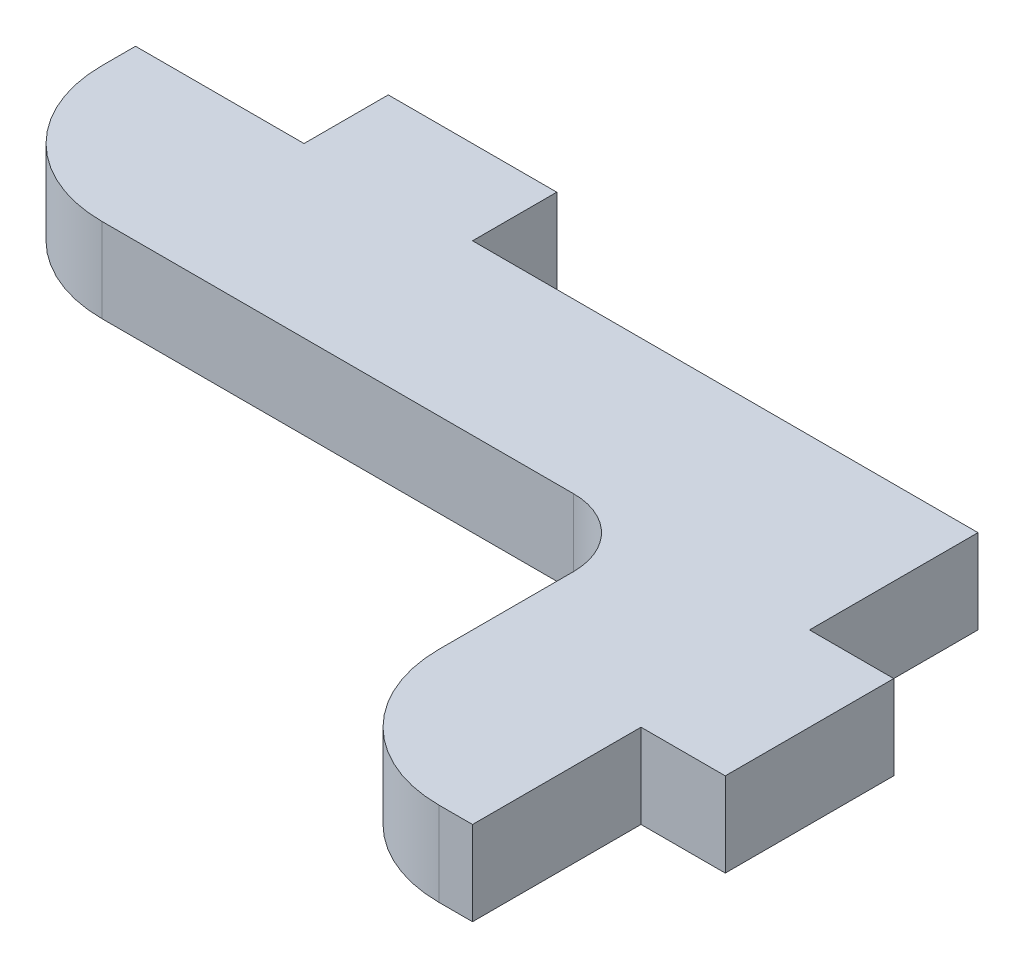
SolidWorks part; units mm, degrees
ref_plane "前视基准面" through (0, 0, 0) normal (0, 0, 1) x (1, 0, 0)
ref_plane "上视基准面" through (0, 0, 0) normal (0, 1, 0) x (1, 0, 0)
ref_plane "右视基准面" through (0, 0, 0) normal (1, 0, 0) x (0, 0, -1)
sketch "草图1" plane through (0, 0, 0) normal (0, 1, 0) x (1, 0, 0)
  line L0 (8, 0) -> (36, 0)
  line L1 (40, -4) -> (40, -12)
  line L2 (48, -20) -> (50, -20)
  line L3 (50, -20) -> (50, -10)
  line L4 (50, 10) -> (20, 10)
  line L5 (0, 10) -> (0, 8)
  line L6 (10, 10) -> (0, 10)
  line L7 (50, 0) -> (50, 10)
  line L8 (10, 10) -> (10, 15)
  line L9 (10, 15) -> (20, 15)
  line L10 (20, 10) -> (20, 15)
  line L11 (50, 0) -> (55, 0)
  line L13 (50, -10) -> (55, -10)
  line L14 (55, 0) -> (55, -10)
  arc A0 (8, 0) -> (0, 8) centre (8, 8) cw
  arc A1 (40, -12) -> (48, -20) centre (48, -12) ccw
  arc A2 (36, 0) -> (40, -4) centre (36, -4) cw
  point P17 (0, 0)
  point P20 (40, -20)
  dimension "D11" = 8
  dimension "D12" = 8
  dimension "D13" = 4
  dimension "D1" = 10
  dimension "D2" = 50
  dimension "D3" = 30
  dimension "D4" = 10
  dimension "D5" = 10
  dimension "D6" = 10
  dimension "D7" = 5
  dimension "D8" = 5
  dimension "D9" = 10
  dimension "D10" = 10
extrude "凸台-拉伸1" add sketch "草图1" along normal blind 5
